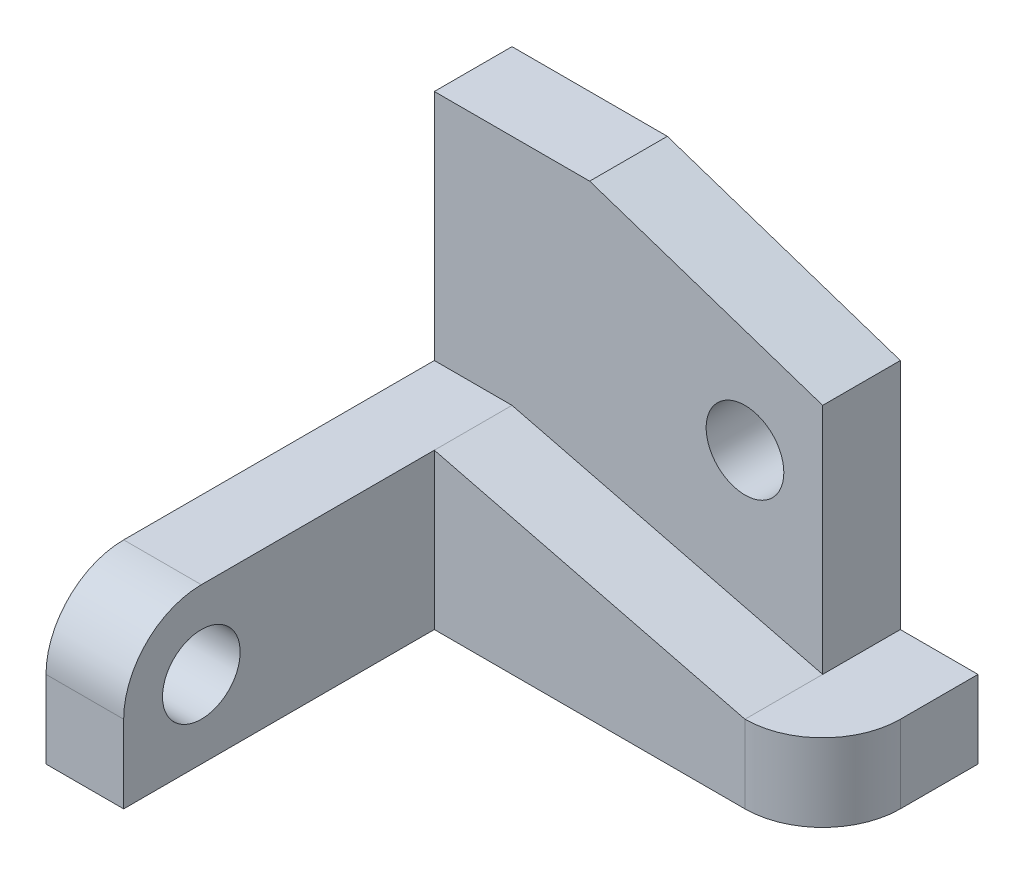
SolidWorks part; units mm, degrees
ref_plane "Front Plane" through (0, 0, 0) normal (0, 0, 1) x (1, 0, 0)
ref_plane "Top Plane" through (0, 0, 0) normal (0, 1, 0) x (1, 0, 0)
ref_plane "Right Plane" through (0, 0, 0) normal (1, 0, 0) x (0, 0, -1)
sketch "Sketch2" plane through (0, 0, 0) normal (0, 0, 1) x (1, 0, 0)
  line L0 (-38.162, 22.2741) -> (-38.162, -27.7259)
  line L1 (-38.162, -27.7259) -> (11.838, -27.7259)
  line L2 (11.838, -27.7259) -> (11.838, 12.2741)
  line L3 (11.838, 12.2741) -> (-18.162, 22.2741)
  line L4 (-18.162, 22.2741) -> (-38.162, 22.2741)
  circle A0 centre (1.838, 2.2741) radius 5
  point P7 (0, 0)
  dimension "D5" = 10
  dimension "D1" = 50
  dimension "D2" = 50
  dimension "D3" = 20
  dimension "D4" = 40
  dimension "D6" = 10
  dimension "D7" = 10
extrude "Boss-Extrude1" add sketch "Sketch2" along normal blind 10
sketch "Sketch4" plane through (-38.162, 0, 0) normal (-1, 0, 0) x (0, 0, 1)
  line L1 (10, -7.7259) -> (50, -7.7259)
  line L2 (10, -7.7259) -> (10, -27.7259)
  line L3 (10, -27.7259) -> (60, -27.7259)
  line L4 (60, -17.7259) -> (60, -27.7259)
  arc A0 (60, -17.7259) -> (50, -7.7259) centre (50, -17.7259) ccw
  circle A1 centre (50, -17.7259) radius 5
  point P7 (60, -7.7259)
  point P12 (55.8732, -27.7259)
  dimension "D3" = 10
  dimension "D4" = 10
  dimension "D1" = 50
  dimension "D2" = 20
  dimension "D5" = 10
  dimension "D6" = 10
extrude "Boss-Extrude2" add sketch "Sketch4" against normal blind 10
sketch "Sketch5" plane through (0, 0, 10) normal (0, 0, 1) x (1, 0, 0)
  line L0 (-28.162, -7.7259) -> (-28.162, -27.7259)
  line L1 (-28.162, -27.7259) -> (21.838, -27.7259)
  line L2 (21.838, -27.7259) -> (21.838, -17.7259)
  line L3 (21.838, -17.7259) -> (11.838, -17.7259)
  line L4 (11.838, -27.7259) -> (11.838, 12.2741) construction
  line L5 (11.838, -17.7259) -> (-28.162, -7.7259)
  dimension "D1" = 10
  dimension "D2" = 10
extrude "Boss-Extrude3" add sketch "Sketch5" against normal mid plane 20 contours L5 L0 L1 L2 L3
sketch "Sketch6" plane through (0, -17.7259, 0) normal (0, 1, 0) x (1, 0, 0)
  line L0 (21.838, 0) -> (21.838, -10)
  line L1 (11.838, -20) -> (4.4623, -20)
  line L2 (11.838, -20) -> (-28.162, -20) construction
  line L3 (21.838, 0) -> (-49.7198, 0)
  line L4 (-49.7198, 0) -> (-49.7198, -63.0847)
  line L5 (-49.7198, -63.0847) -> (4.4623, -63.0847)
  line L6 (4.4623, -63.0847) -> (4.4623, -20)
  arc A0 (21.838, -10) -> (11.838, -20) centre (11.838, -10) cw
  point P10 (21.838, -20)
  dimension "D1" = 10
extrude "Cut-Extrude1" cut sketch "Sketch6" against normal blind 20 flip side to cut
